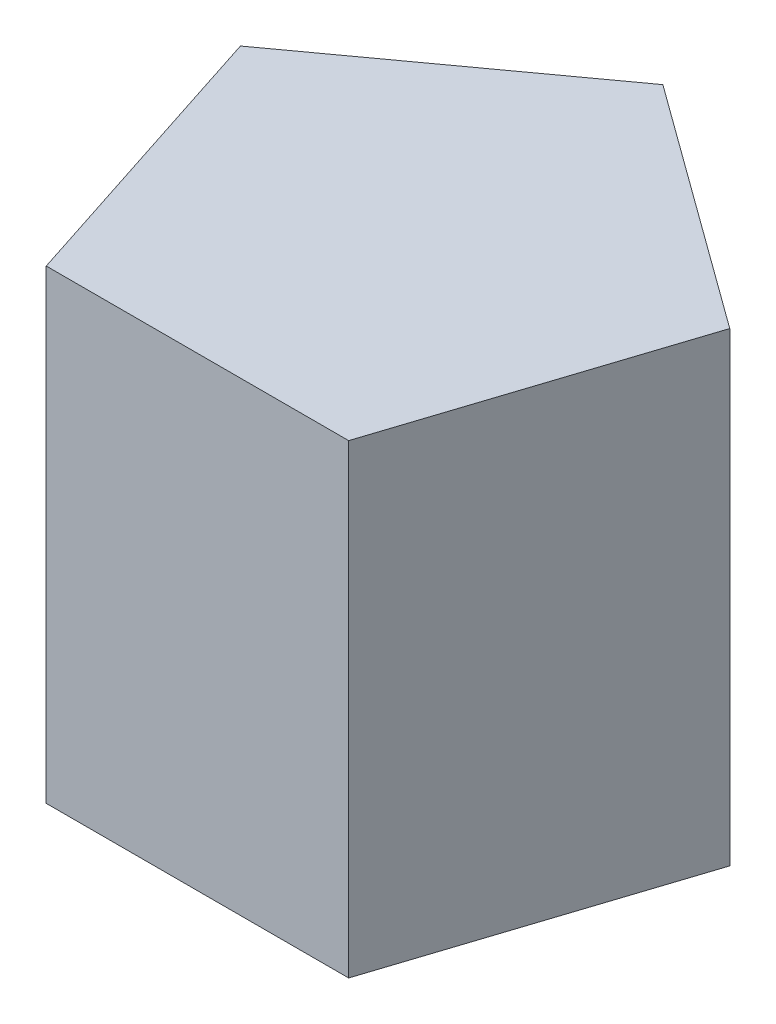
SolidWorks part; units mm, degrees
material "ABS"
ref_plane "Front Plane" through (0, 0, 0) normal (0, 0, 1) x (1, 0, 0)
ref_plane "Top Plane" through (0, 0, 0) normal (0, 1, 0) x (1, 0, 0)
ref_plane "Right Plane" through (0, 0, 0) normal (1, 0, 0) x (0, 0, -1)
sketch "Sketch1" plane through (0, 0, 0) normal (0, 1, 0) x (1, 0, 0)
  line L0 (-26.2866, 8.541) -> (26.2866, 8.541) construction
  line L1 (-26.2866, 8.541) -> (-16.246, -22.3607)
  line L2 (-16.246, -22.3607) -> (16.246, -22.3607)
  line L3 (16.246, -22.3607) -> (26.2866, 8.541)
  line L4 (26.2866, 8.541) -> (0, 27.6393)
  line L5 (0, 27.6393) -> (-26.2866, 8.541)
  circle A0 centre (0, 0) radius 22.3607 construction
  dimension "D1" = 50
extrude "Boss-Extrude1" add sketch "Sketch1" along normal mid plane 50
